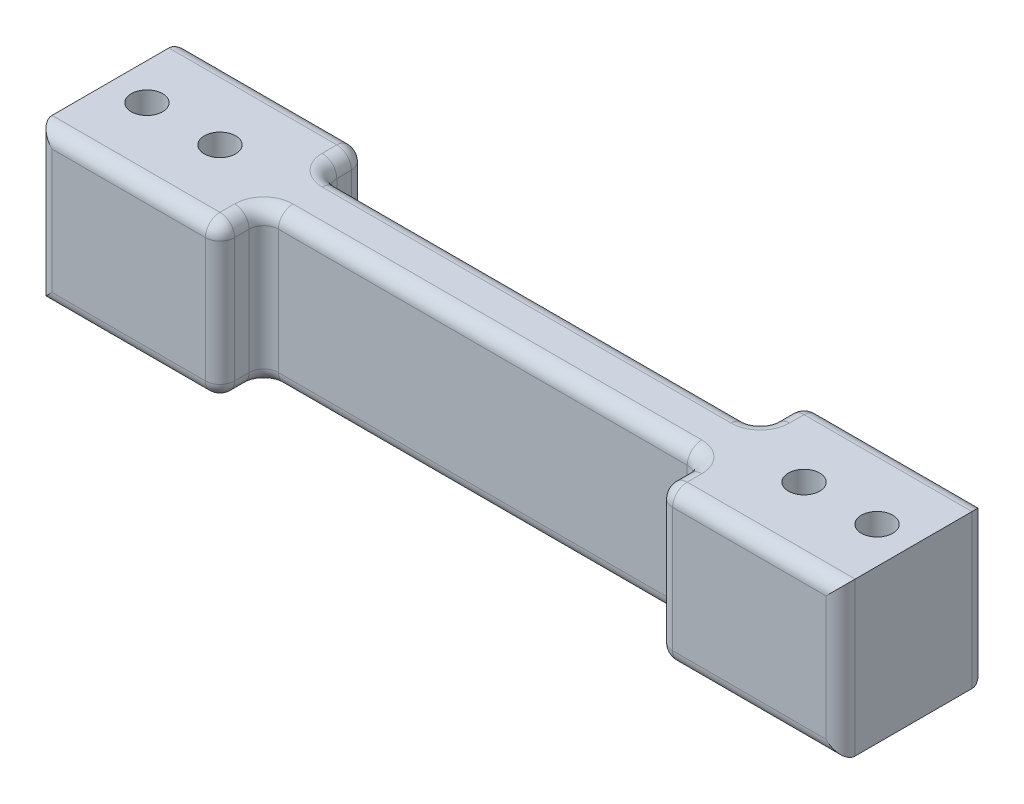
SolidWorks part; units mm, degrees
ref_plane "前视基准面" through (0, 0, 0) normal (0, 0, 1) x (1, 0, 0)
ref_plane "上视基准面" through (0, 0, 0) normal (0, 1, 0) x (1, 0, 0)
ref_plane "右视基准面" through (0, 0, 0) normal (1, 0, 0) x (0, 0, -1)
other "Configuration Table"
sketch "草图1" plane through (0, 0, 0) normal (0, 0, 1) x (1, 0, 0)
  line L1 (0, 0) -> (-110, 0)
  line L2 (0, 0) -> (0, 21)
  line L3 (0, 21) -> (-110, 21)
  line L4 (-110, 0) -> (-110, 21)
  dimension "D1" = 21
  dimension "D2" = 110
extrude "凸台-拉伸1" add sketch "草图1" along normal blind 20
sketch "草图2" plane through (0, 21, 0) normal (0, 1, 0) x (1, 0, 0)
  line L3 (0, -10) -> (-110, -10) construction
  line L4 (0, -20) -> (0, 0) construction
  line L5 (-110, -20) -> (-110, 0) construction
  circle A1 centre (-15, -10) radius 2.15
  circle A2 centre (-5, -10) radius 2.15
  circle A3 centre (-105, -10) radius 2.15
  circle A4 centre (-95, -10) radius 2.15
  dimension "D1" = 4.3
  dimension "D2" = 4.3
  dimension "D3" = 5
  dimension "D4" = 10
  dimension "D5" = 10
  dimension "D6" = 90
extrude "切除-拉伸1" cut sketch "草图2" against normal up to next
sketch "草图3" plane through (0, 21, 0) normal (0, 1, 0) x (1, 0, 0)
  line L0 (0, 0) -> (-110, 0) construction
  line L1 (-85, 0) -> (-25, 0)
  line L2 (-85, 0) -> (-85, -6)
  line L3 (-85, -6) -> (-25, -6)
  line L4 (-25, 0) -> (-25, -6)
  line L5 (0, -10) -> (-110, -10) construction
  line L6 (0, -20) -> (0, 0) construction
  line L7 (-110, -20) -> (-110, 0) construction
  line L8 (-55, -20) -> (-55, -49.5242) construction
  line L9 (0, -20) -> (-110, -20) construction
  line L10 (-25, -20) -> (-25, -14)
  line L11 (-85, -20) -> (-25, -20)
  line L12 (-85, -20) -> (-85, -14)
  line L13 (-85, -14) -> (-25, -14)
  dimension "D1" = 60
  dimension "D2" = 6
extrude "切除-拉伸2" cut sketch "草图3" against normal up to next
fillet "圆角2" radius 2 32 edges at (-110, 10.5, 0) (-97.5, 0, 0) (-97.5, 21, 0) (0, 10.5, 0) (-12.5, 21, 0) (-12.5, 0, 0) (-97.5, 0, 20) (-110, 10.5, 20) (-97.5, 21, 20) (-12.5, 21, 20) (0, 10.5, 20) (-12.5, 0, 20) (-25, 10.5, 0) (-25, 21, 3) (-25, 0, 3) (-85, 21, 3) (-85, 10.5, 0) (-85, 0, 3) (-25, 10.5, 6) (-55, 21, 6) (-85, 10.5, 6) (-55, 0, 6) (-25, 21, 17) (-25, 10.5, 20) (-25, 0, 17) (-85, 10.5, 20) (-85, 21, 17) (-85, 0, 17) (-85, 10.5, 14) (-55, 21, 14) (-25, 10.5, 14) (-55, 0, 14)
